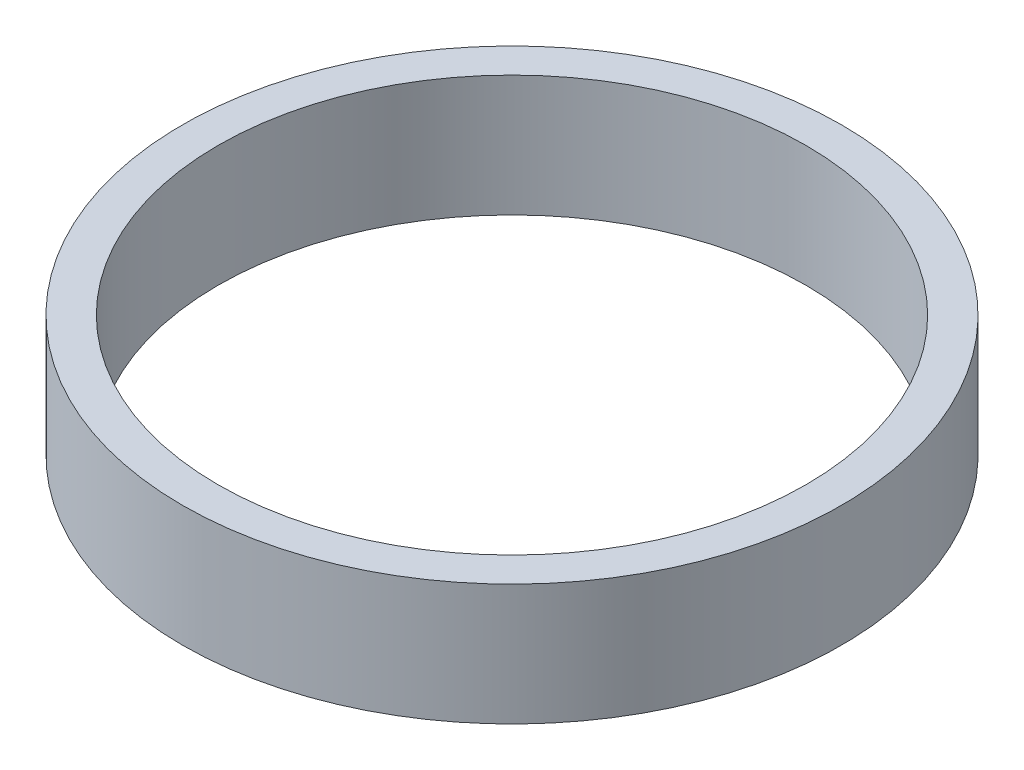
SolidWorks part; units mm, degrees
ref_plane "Plan de face" through (0, 0, 0) normal (0, 0, 1) x (1, 0, 0)
ref_plane "Plan de dessus" through (0, 0, 0) normal (0, 1, 0) x (1, 0, 0)
ref_plane "Plan de droite" through (0, 0, 0) normal (1, 0, 0) x (0, 0, -1)
sketch "Sketch1" plane through (0, 0, 0) normal (0, 1, 0) x (1, 0, 0)
  circle A0 centre (0, 0) radius 4.625
  circle A1 centre (0, 0) radius 4.125
  dimension "D1" = 8.25
  dimension "D2" = 9.25
extrude "Boss-Extrude1" add sketch "Sketch1" along normal blind 1.7
